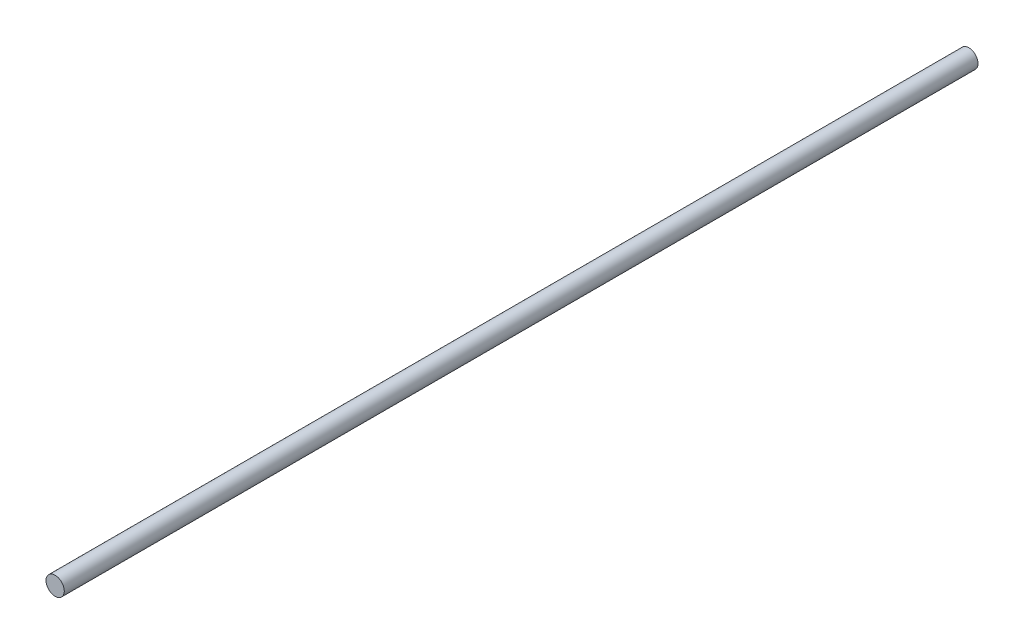
SolidWorks part; units mm, degrees
ref_plane "Front Plane" through (0, 0, 0) normal (0, 0, 1) x (1, 0, 0)
ref_plane "Top Plane" through (0, 0, 0) normal (0, 1, 0) x (1, 0, 0)
ref_plane "Right Plane" through (0, 0, 0) normal (1, 0, 0) x (0, 0, -1)
sketch "Sketch1" plane through (0, 0, 0) normal (0, 0, 1) x (1, 0, 0)
  circle A0 centre (0, 0) radius 1
  dimension "D1" = 2
extrude "Boss-Extrude1" add sketch "Sketch1" along normal blind 100
